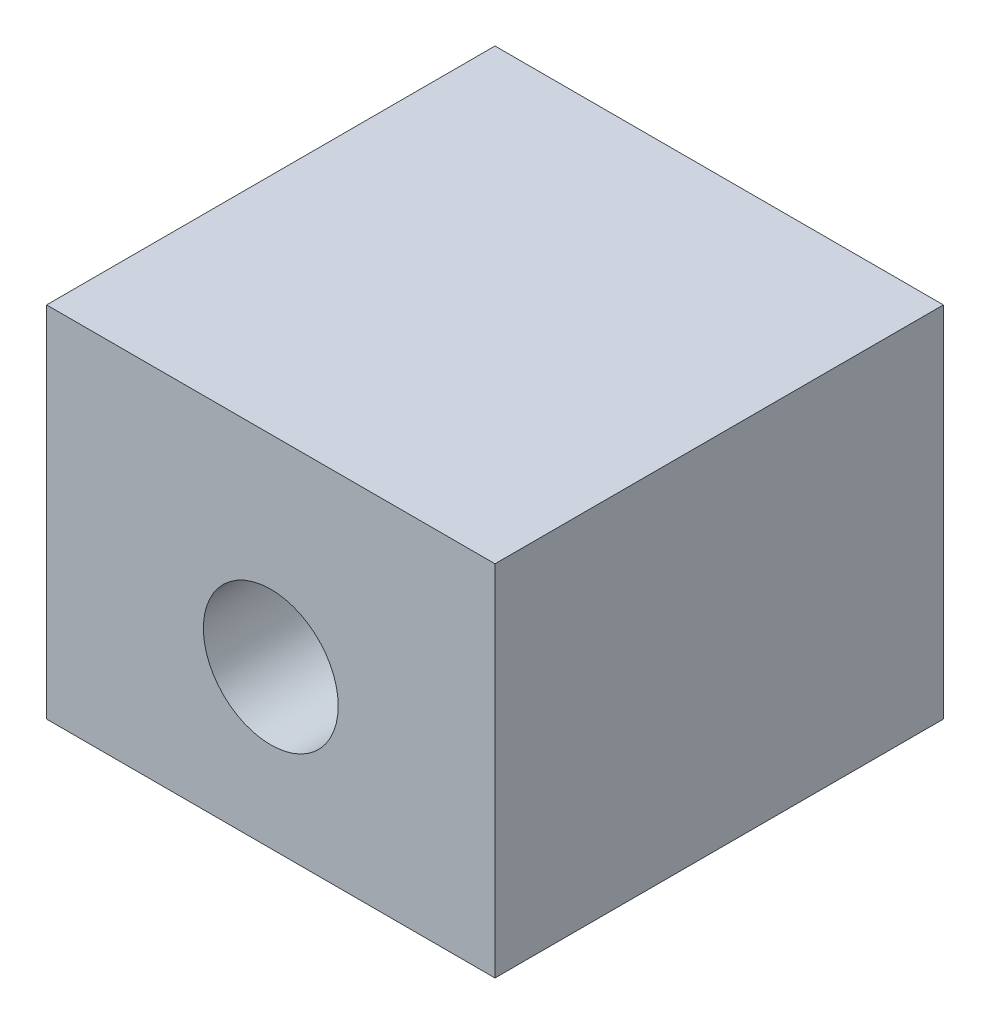
SolidWorks part; units mm, degrees
material "6061-T4 (SS)"
ref_plane "Front Plane" through (0, 0, 0) normal (0, 0, 1) x (1, 0, 0)
ref_plane "Top Plane" through (0, 0, 0) normal (0, 1, 0) x (1, 0, 0)
ref_plane "Right Plane" through (0, 0, 0) normal (1, 0, 0) x (0, 0, -1)
sketch "Sketch1" plane through (0, 0, 0) normal (0, 1, 0) x (1, 0, 0)
  line L1 (-5, 5) -> (5, 5)
  line L2 (-5, 5) -> (-5, -5)
  line L3 (-5, -5) -> (5, -5)
  line L4 (5, 5) -> (5, -5)
  line L5 (-5, 5) -> (5, -5) construction
  line L6 (-5, -5) -> (5, 5) construction
  point P0 (0, 0)
  dimension "D1" = 10
  dimension "D2" = 10
extrude "Boss-Extrude1" add sketch "Sketch1" along normal blind 8
sketch "Sketch2" plane through (0, 0, 5) normal (0, 0, 1) x (1, 0, 0)
  line L0 (0, 9.2809) -> (0, -1.27) construction
  line L1 (-5, 3.5054) -> (5.741, 3.5054) construction
  circle A0 centre (0, 3.5054) radius 1.5033
extrude "Cut-Extrude1" cut sketch "Sketch2" against normal blind 10
